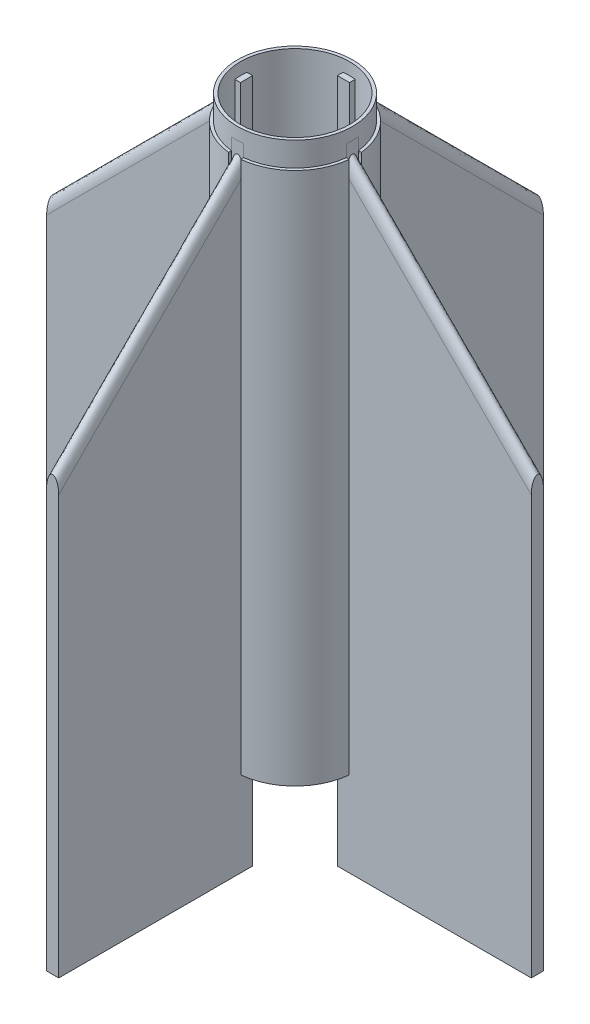
SolidWorks part; units mm, degrees
ref_plane "Спереди" through (0, 0, 0) normal (0, 0, 1) x (1, 0, 0)
ref_plane "Сверху" through (0, 0, 0) normal (0, 1, 0) x (1, 0, 0)
ref_plane "Справа" through (0, 0, 0) normal (1, 0, 0) x (0, 0, -1)
sketch "Эскиз1" plane through (0, 0, 0) normal (0, 1, 0) x (1, 0, 0)
  circle A0 centre (0, 0) radius 25
  circle A1 centre (0, 0) radius 19.15
  dimension "D1" = 50
  dimension "D2" = 38.3
extrude "Бобышка-Вытянуть1" add sketch "Эскиз1" along normal blind 40
sketch "Эскиз2" plane through (0, 40, 0) normal (0, 1, 0) x (1, 0, 0)
  circle A0 centre (0, 0) radius 25
  circle A1 centre (0, 0) radius 24
  dimension "D1" = 50
  dimension "D2" = 48
extrude "Бобышка-Вытянуть2" add sketch "Эскиз2" along normal blind 100
sketch "Эскиз4" plane through (0, 140, 0) normal (0, 1, 0) x (1, 0, 0)
  circle A0 centre (0, 0) radius 25
  circle A1 centre (0, 0) radius 19.15
  dimension "D1" = 50
  dimension "D2" = 38.3
extrude "Бобышка-Вытянуть3" add sketch "Эскиз4" along normal blind 40
sketch "Эскиз5" plane through (0, 180, 0) normal (0, 1, 0) x (1, 0, 0)
  circle A0 centre (0, 0) radius 25
  circle A1 centre (0, 0) radius 22.5
  dimension "D1" = 50
  dimension "D2" = 45
extrude "Бобышка-Вытянуть4" add sketch "Эскиз5" along normal blind 40
sketch "Эскиз6" plane through (0, 220, 0) normal (0, 1, 0) x (1, 0, 0)
  circle A0 centre (0, 0) radius 22.5
  circle A1 centre (0, 0) radius 23.8
  dimension "D1" = 45
  dimension "D2" = 47.6
extrude "Бобышка-Вытянуть5" add sketch "Эскиз6" along normal blind 10
sketch "Эскиз8" plane through (0, 0, 0) normal (0, 0, 1) x (1, 0, 0)
  line L0 (0, 273.9435) -> (0, 90) construction
  line L1 (-25, 0) -> (25, 0) construction
  line L2 (2.5, 225) -> (-2.5, 225)
  line L3 (2.5, 225) -> (2.5, -45)
  line L4 (2.5, -45) -> (-2.5, -45)
  line L5 (-2.5, 225) -> (-2.5, -45)
  line L6 (2.5, 225) -> (-2.5, -45) construction
  line L7 (2.5, -45) -> (-2.5, 225) construction
  point P3 (0, 90)
  dimension "D1" = 5
  dimension "D2" = 270
  dimension "D3" = 90
extrude "Бобышка-Вытянуть6" add sketch "Эскиз8" against normal blind 80 from offset 20 offset against normal yes
sketch "Эскиз10" plane through (2.5, 0, 0) normal (1, 0, 0) x (0, 0, -1)
  line L0 (20, -35) -> (100, -35)
  line L1 (20, -45) -> (20, 0) construction
  line L2 (100, -45) -> (100, 225) construction
  line L3 (100, -45) -> (20, -45) construction
  line L4 (20, -35) -> (20, -45)
  line L5 (20, -45) -> (100, -45)
  line L6 (100, -45) -> (100, -35)
  dimension "D1" = 10
extrude "Вырез-Вытянуть2" cut sketch "Эскиз10" against normal blind 80
sketch "Эскиз12" plane through (2.5, 0, 0) normal (1, 0, 0) x (0, 0, -1)
  line L0 (24.8747, 220) -> (23.6683, 220)
  line L1 (23.6683, 220) -> (23.6683, 225)
  line L2 (23.6683, 225) -> (100, 225)
  line L3 (100, 225) -> (100, 144.8747)
  line L4 (100, -35) -> (100, 225) construction
  line L5 (100, 144.8747) -> (24.8747, 220)
  line L6 (24.8747, 0) -> (24.8747, 220) construction
  dimension "D1" = 45
extrude "Вырез-Вытянуть3" cut sketch "Эскиз12" against normal blind 80
sketch "Эскиз13" plane through (0, 122.4373, -122.4373) normal (0, 0.7071, -0.7071) x (1, 0, 0)
  line L2 (0, -141.7312) -> (0, -31.7312)
  line L4 (-2.5, -31.7312) -> (2.5, -31.7312) construction
  dimension "D1" = 110
sketch "Эскиз14" plane through (0, 0, -23.6683) normal (0, 0, -1) x (-1, 0, 0)
  line L0 (0, 141644.1894) -> (0, 141626.1785) construction
  line L2 (2.5, 220) -> (-2.5, 220) construction
  line L3 (2.5, 220) -> (-2.5, 220) construction
  line L5 (2.5, 220) -> (2.5, 0) construction
  line L7 (-2.5, 214) -> (-2.5, 220)
  line L10 (2.5, 220) -> (2.5, 214)
  line L11 (-2.5, 220) -> (-2.5, 225)
  line L12 (-2.5, 225) -> (2.5, 225)
  line L13 (2.5, 225) -> (2.5, 220)
  ellipse E0 centre (0, 214) end of major axis (0, 220) minor radius 2.5 (2.5, 214) -> (-2.5, 214) ccw
  point P3 (0, 220)
  dimension "D1" = 6
sweep "Вырез-По траектории10" cut profiles "Эскиз14" path "Эскиз13"
pattern_circular "Круговой массив1" count 4 over 360 about axis through (0, 40, 0) along (0, -1, 0) of "Бобышка-Вытянуть6", "Вырез-По траектории10", "Вырез-Вытянуть3", "Вырез-Вытянуть2"
